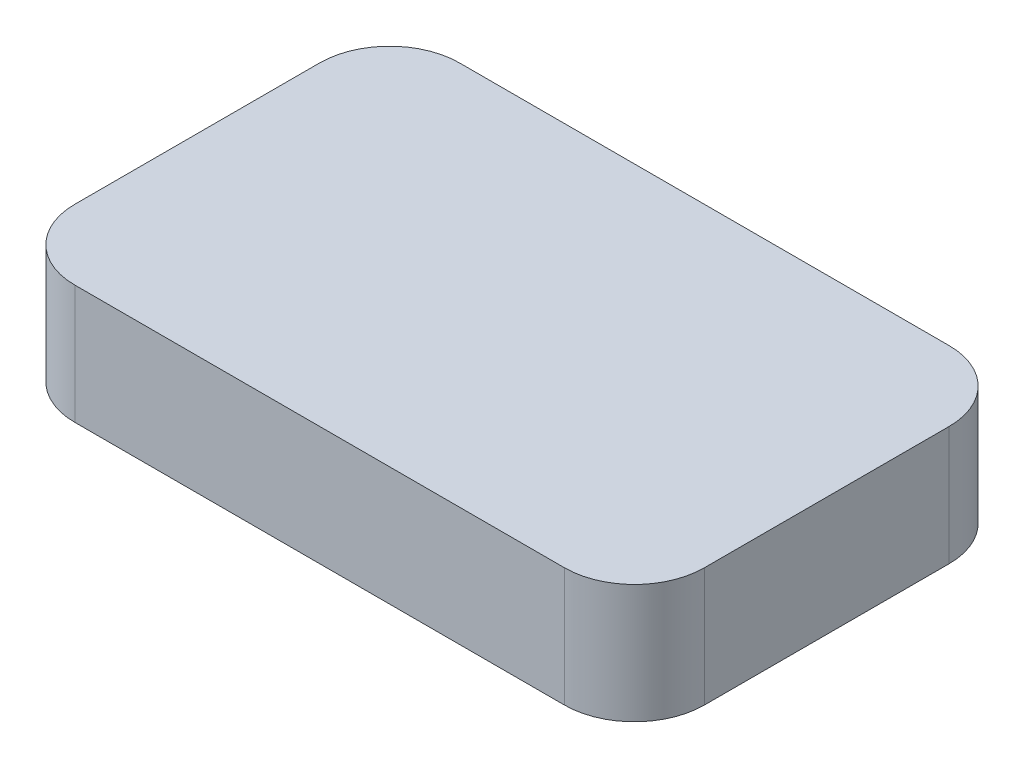
SolidWorks part; units mm, degrees
ref_plane "Front Plane" through (0, 0, 0) normal (0, 0, 1) x (1, 0, 0)
ref_plane "Top Plane" through (0, 0, 0) normal (0, 1, 0) x (1, 0, 0)
ref_plane "Right Plane" through (0, 0, 0) normal (1, 0, 0) x (0, 0, -1)
sketch "Sketch1" plane through (0, 0, 0) normal (0, 1, 0) x (1, 0, 0)
  line L0 (0, 27.5) -> (0, -27.5) construction
  line L1 (-35, 27.5) -> (35, 27.5)
  line L2 (-45, 17.5) -> (-45, -17.5)
  line L3 (-35, -27.5) -> (35, -27.5)
  line L4 (45, 17.5) -> (45, -17.5)
  arc A0 (35, 27.5) -> (45, 17.5) centre (35, 17.5) cw
  arc A1 (45, -17.5) -> (35, -27.5) centre (35, -17.5) cw
  arc A2 (-35, -27.5) -> (-45, -17.5) centre (-35, -17.5) cw
  arc A3 (-45, 17.5) -> (-35, 27.5) centre (-35, 17.5) cw
  dimension "D1" = 10
  dimension "D2" = 90
  dimension "D3" = 55
extrude "Boss-Extrude1" add sketch "Sketch1" along normal blind 17
